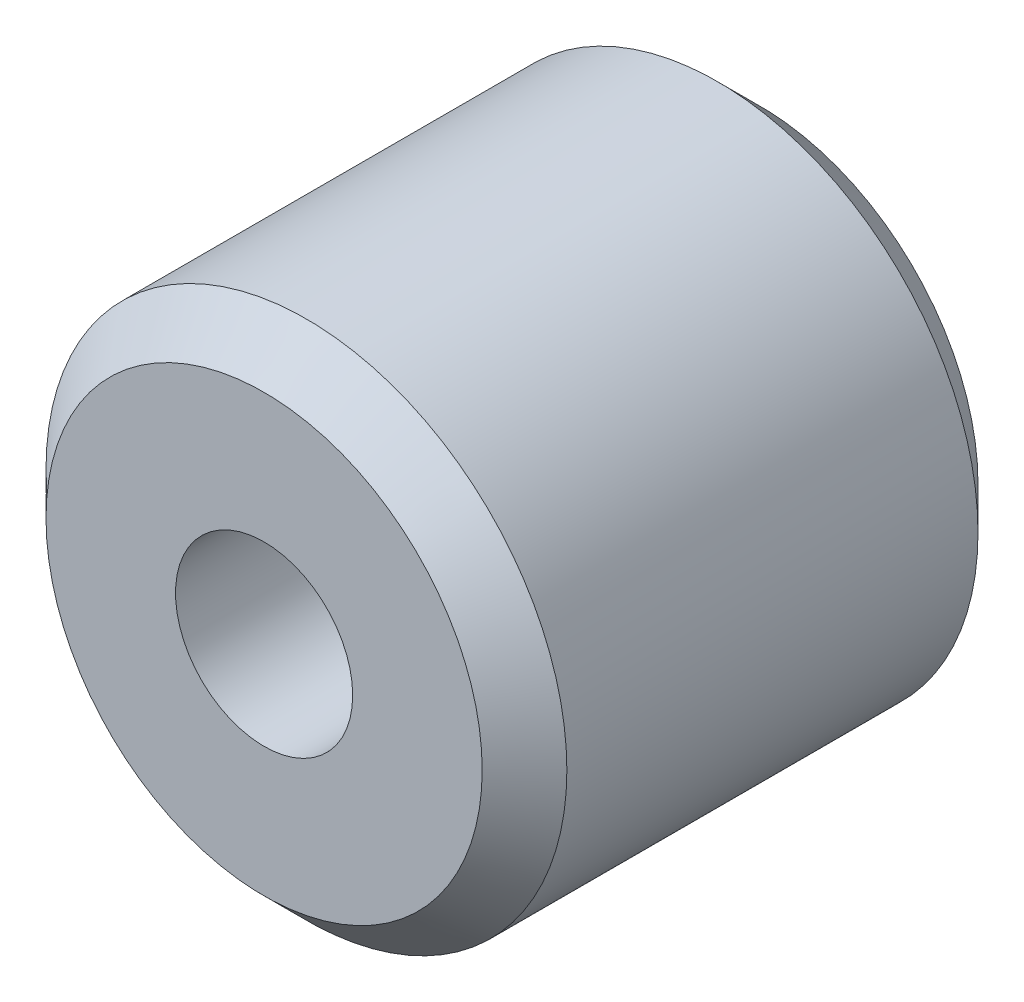
SolidWorks part; units mm, degrees
ref_plane "Front Plane" through (0, 0, 0) normal (0, 0, 1) x (1, 0, 0)
ref_plane "Top Plane" through (0, 0, 0) normal (0, 1, 0) x (1, 0, 0)
ref_plane "Right Plane" through (0, 0, 0) normal (1, 0, 0) x (0, 0, -1)
sketch "Sketch1" plane through (0, 0, 0) normal (0, 0, 1) x (1, 0, 0)
  circle A0 centre (0, 0) radius 4.675
  circle A1 centre (0, 0) radius 1.59
  dimension "D1" = 9.35
  dimension "D2" = 3.18
extrude "Boss-Extrude1" add sketch "Sketch1" along normal mid plane 8.9
chamfer "Chamfer1" distance 0.76 angle 45 2 edges at (4.675, 0, -4.45) (4.675, 0, 4.45)
